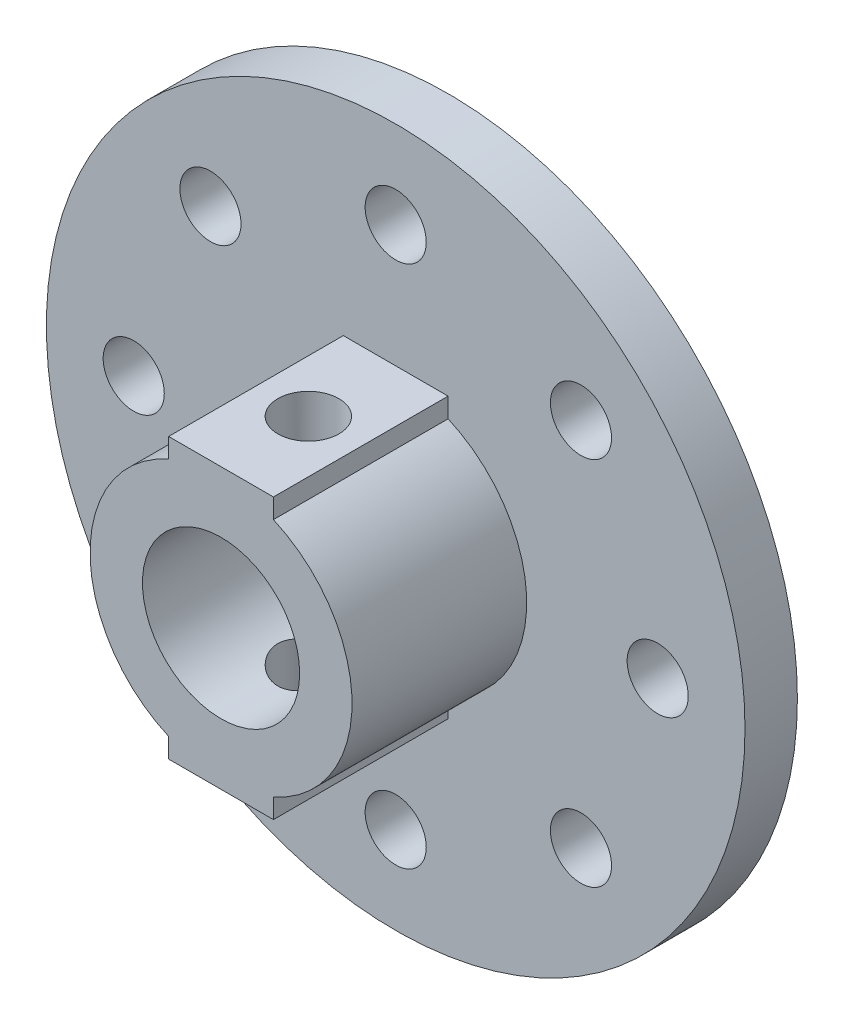
SolidWorks part; units mm, degrees
ref_plane "Front Plane" through (0, 0, 0) normal (0, 0, 1) x (1, 0, 0)
ref_plane "Top Plane" through (0, 0, 0) normal (0, 1, 0) x (1, 0, 0)
ref_plane "Right Plane" through (0, 0, 0) normal (1, 0, 0) x (0, 0, -1)
sketch "Sketch1" plane through (0, 0, 0) normal (0, 0, 1) x (1, 0, 0)
  circle A0 centre (0, 0) radius 20
  dimension "D1" = 40
extrude "Boss-Extrude1" add sketch "Sketch1" along normal blind 3
sketch "Sketch2" plane through (0, 0, 3) normal (0, 0, 1) x (1, 0, 0)
  circle A0 centre (0, 0) radius 7.5
  dimension "D1" = 15
extrude "Boss-Extrude2" add sketch "Sketch2" along normal blind 10
sketch "Sketch6" plane through (0, 0, 3) normal (0, 0, 1) x (1, 0, 0)
  line L1 (-3, 8) -> (3, 8)
  line L2 (-3, 8) -> (-3, -8)
  line L3 (-3, -8) -> (3, -8)
  line L4 (3, 8) -> (3, -8)
  line L5 (-3, 8) -> (3, -8) construction
  line L6 (-3, -8) -> (3, 8) construction
  point P0 (0, 0)
  dimension "D1" = 16
  dimension "D2" = 6
extrude "Boss-Extrude3" add sketch "Sketch6" along normal blind 10
sketch "Sketch3" plane through (0, 0, 13) normal (0, 0, 1) x (1, 0, 0)
  circle A0 centre (0, 0) radius 4.5
  dimension "D1" = 9
extrude "Cut-Extrude1" cut sketch "Sketch3" against normal through all
sketch "Sketch4" plane through (0, 0, 3) normal (0, 0, 1) x (1, 0, 0)
  line L0 (0, 0) -> (0, 15) construction
  circle A0 centre (0, 15) radius 1.75
  circle A1 centre (10.6066, 10.6066) radius 1.75
  circle A2 centre (15, 0) radius 1.75
  circle A3 centre (10.6066, -10.6066) radius 1.75
  circle A4 centre (0, -15) radius 1.75
  circle A5 centre (-10.6066, -10.6066) radius 1.75
  circle A6 centre (-15, 0) radius 1.75
  circle A7 centre (-10.6066, 10.6066) radius 1.75
  point P21 (0, 0)
  dimension "D2" = 3.5
  dimension "D1" = 15
  dimension "D3" = 8
extrude "Cut-Extrude2" cut sketch "Sketch4" against normal through all
sketch "Sketch5" plane through (0, 0, 0) normal (0, 1, 0) x (1, 0, 0)
  line L0 (-7.5, -8) -> (7.5, -8) construction
  line L3 (-7.5, -3) -> (-7.5, -13) construction
  line L4 (7.5, -13) -> (7.5, -3) construction
  circle A0 centre (0, -8) radius 1.75
  point P4 (-7.5, -8)
  point P7 (7.5, -8)
  point P8 (-1.4248, -8.8155)
  dimension "D1" = 3.5
extrude "Cut-Extrude3" cut sketch "Sketch5" against normal through all both and the other way through all
